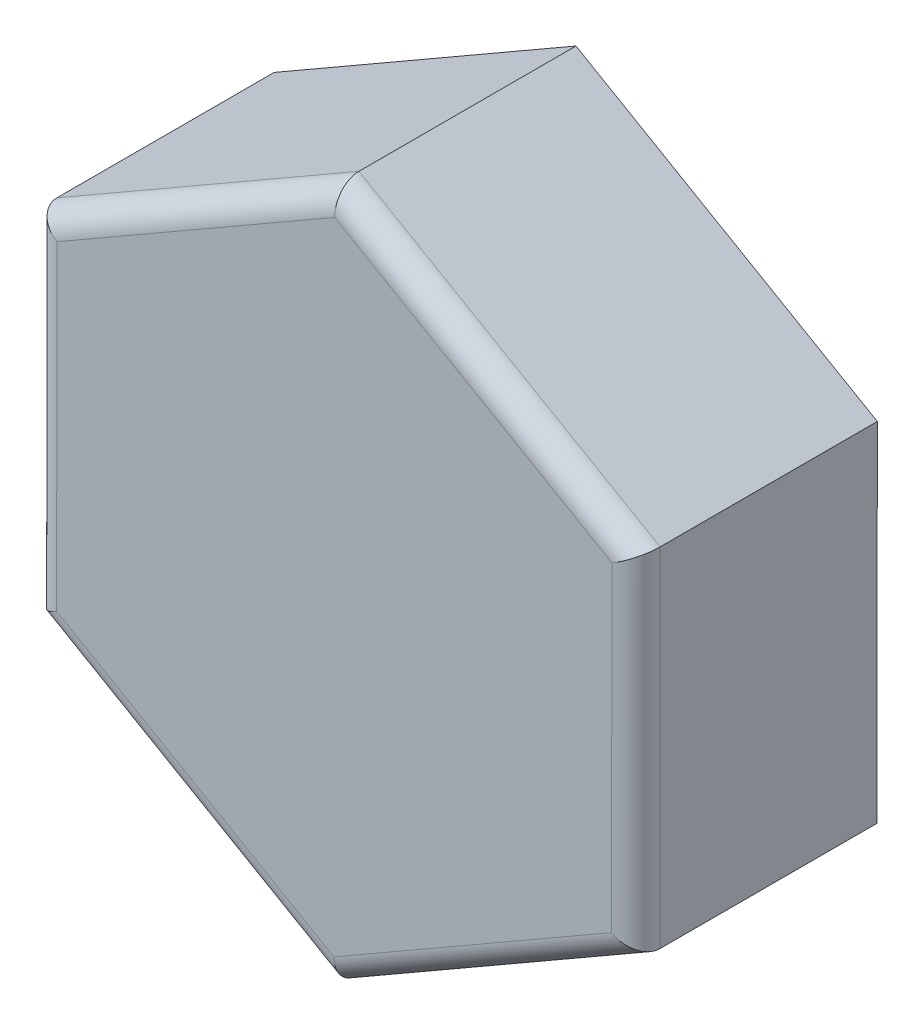
SolidWorks part; units mm, degrees
ref_plane "Front Plane" through (0, 0, 0) normal (0, 0, 1) x (1, 0, 0)
ref_plane "Top Plane" through (0, 0, 0) normal (0, 1, 0) x (1, 0, 0)
ref_plane "Right Plane" through (0, 0, 0) normal (1, 0, 0) x (0, 0, -1)
sketch "Sketch1" plane through (0, 0, 0) normal (0, 0, 1) x (1, 0, 0)
  line L1 (-1.9212, -0.6102) -> (-1.9195, 0.8331)
  line L2 (-1.9195, 0.8331) -> (-3.1686, 1.5563)
  line L3 (-3.1686, 1.5563) -> (-4.4195, 0.8361)
  line L4 (-4.4195, 0.8361) -> (-4.4212, -0.6072)
  line L5 (-4.4212, -0.6072) -> (-3.1721, -1.3304)
  line L6 (-3.1721, -1.3304) -> (-1.9212, -0.6102)
  circle A0 centre (-3.1703, 0.1129) radius 1.25 construction
  dimension "D1" = 2.5
extrude "Boss-Extrude1" add sketch "Sketch1" along normal blind 1
fillet "Fillet1" radius 0.1 6 edges at (-3.7966, -0.9688, 1) (-4.4203, 0.1144, 1) (-3.794, 1.1962, 1) (-2.544, 1.1947, 1) (-1.9203, 0.1114, 1) (-2.5466, -0.9703, 1)
ref_plane "Plane1" through (0, 0, 0) normal (0, 0, -1) x (-1, 0, 0)
sketch "Sketch2" plane through (0, 0, 0) normal (0, 0, -1) x (-1, 0, 0)
  line L0 (1.9212, -0.6102) -> (1.9195, 0.8331) construction
  line L1 (4.4212, -0.6072) -> (3.1721, -1.3304) construction
  line L2 (3.1721, -1.3304) -> (1.9212, -0.6102) construction
  circle A0 centre (3.1703, 0.1129) radius 0.8
  dimension "D1" = 1.25
  dimension "D2" = 1.25
  dimension "D3" = 1.25
extrude "Cut-Extrude1" cut sketch "Sketch2" against normal blind 0.01
